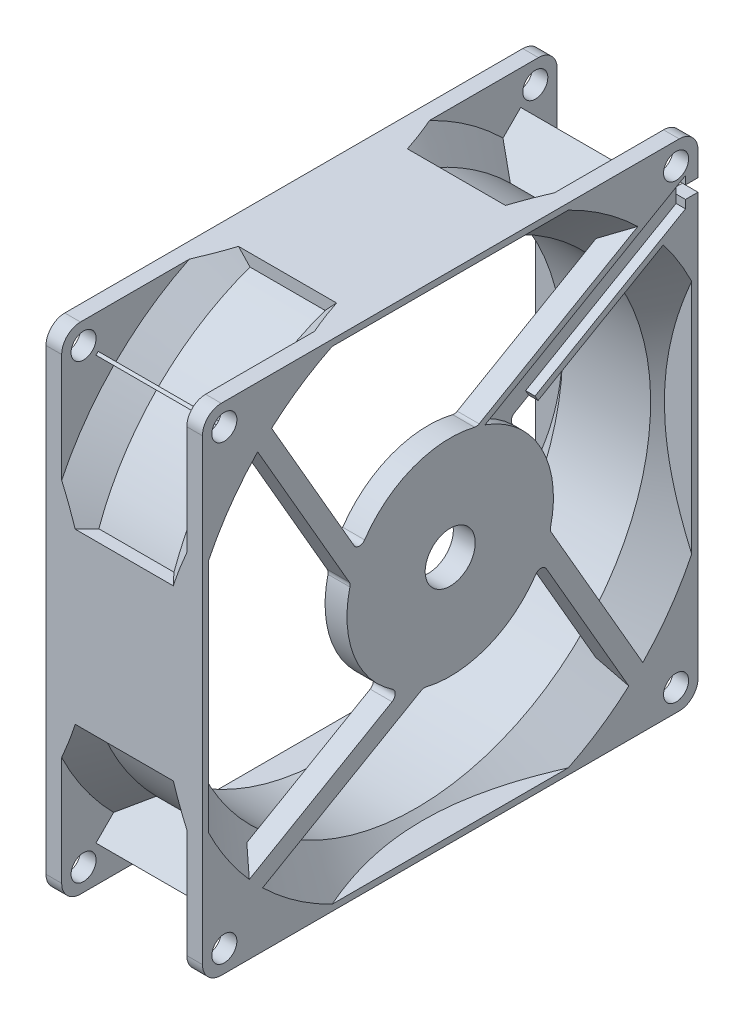
SolidWorks part; units mm, degrees
ref_plane "Front Plane" through (0, 0, 0) normal (0, 0, 1) x (1, 0, 0)
ref_plane "Top Plane" through (0, 0, 0) normal (0, 1, 0) x (1, 0, 0)
ref_plane "Right Plane" through (0, 0, 0) normal (1, 0, 0) x (0, 0, -1)
sketch "Sketch1" plane through (0, 0, 0) normal (0, 0, 1) x (1, 0, 0)
  line L0 (-10, 56) -> (-10, 44)
  line L1 (-10, 44) -> (-6, 40)
  line L2 (-6, 40) -> (6, 40)
  line L3 (6, 40) -> (10, 44)
  line L4 (10, 44) -> (10, 56)
  line L5 (-12.5, 56) -> (-12.5, 42.9645)
  line L6 (-12.5, 42.9645) -> (-7.0355, 37.5)
  line L7 (-7.0355, 37.5) -> (7.0355, 37.5)
  line L8 (7.0355, 37.5) -> (12.5, 42.9645)
  line L9 (12.5, 42.9645) -> (12.5, 56)
  line L10 (-12.5, 56) -> (-10, 56)
  line L11 (10, 56) -> (12.5, 56)
  line L12 (-12.5, 0) -> (13.9887, 0) construction
  point P8 (0, 40)
  dimension "D1" = 12
  dimension "D2" = 4
  dimension "D3" = 12
  dimension "D4" = 45
  dimension "D5" = 40
  dimension "D6" = 45
  dimension "D7" = 2.5
revolve "Revolve1" add sketch "Sketch1" angle 360 about L12
sketch "Sketch2" plane through (12.5, 0, 0) normal (1, 0, 0) x (0, 0, -1)
  line L1 (-39.598, 39.598) -> (39.598, 39.598)
  line L2 (-39.598, 39.598) -> (-39.598, -39.598)
  line L3 (-39.598, -39.598) -> (39.598, -39.598)
  line L4 (39.598, 39.598) -> (39.598, -39.598)
  line L5 (-39.598, 39.598) -> (39.598, -39.598) construction
  line L6 (-39.598, -39.598) -> (39.598, 39.598) construction
  circle A0 centre (0, 0) radius 56 construction
  point P0 (0, 0)
extrude "Cut-Extrude1" cut sketch "Sketch2" against normal through all flip side to cut
sketch "Sketch3" plane through (12.5, 0, 0) normal (1, 0, 0) x (0, 0, -1)
  line L0 (-16.6717, 39.598) -> (-39.598, 39.598) construction
  line L1 (-18.8717, 39.598) -> (18.8717, 39.598)
  line L2 (-18.8717, 39.598) -> (-18.8717, 38.598)
  line L3 (-18.8717, 38.598) -> (18.8717, 38.598)
  line L4 (18.8717, 39.598) -> (18.8717, 38.598)
  arc A0 (39.598, 16.6717) -> (16.6717, 39.598) centre (0, 0) ccw construction
  arc A2 (-16.6717, 39.598) -> (-39.598, 16.6717) centre (0, 0) ccw construction
  dimension "D1" = 1
extrude "Boss-Extrude1" add sketch "Sketch3" against normal up to body
pattern_circular "CirPattern1" count 4 over 360 about axis through (0, 0, 0) along (1, 0, 0) of "Boss-Extrude1"
mirror "Mirror1" about plane through (0, 0, 0) normal (1, 0, 0) of "CirPattern1", "Boss-Extrude1"
sketch "Sketch4" plane through (0, 0, 0) normal (1, 0, 0) x (0, 0, -1)
  line L0 (0, 0) -> (39.598, 39.598) construction
  line L1 (33.7643, 34.1179) -> (26.3391, 26.6927)
  line L2 (33.7643, 34.1179) -> (34.1179, 33.7643)
  line L3 (26.3391, 26.6927) -> (26.6927, 26.3391)
  line L4 (34.1179, 33.7643) -> (26.6927, 26.3391)
  circle A0 centre (0, 0) radius 37.5 construction
  point P4 (26.5159, 26.5159)
  point P14 (33.9411, 33.9411)
  dimension "D1" = 0.5
  dimension "D2" = 48
extrude "Boss-Extrude2" add sketch "Sketch4" along normal up to body and the other way up to body
pattern_circular "CirPattern2" count 4 over 360 about axis through (0, 0, 0) along (1, 0, 0) of "Boss-Extrude2"
sketch "Sketch5" plane through (12.5, 0, 0) normal (1, 0, 0) x (0, 0, -1)
  line L0 (-39.598, -39.598) -> (39.598, -39.598) construction
  line L1 (39.598, -39.598) -> (39.598, 39.598) construction
  circle A0 centre (36.098, -36.098) radius 2
  dimension "D1" = 4
  dimension "D2" = 3.5
  dimension "D3" = 3.5
extrude "Cut-Extrude2" cut sketch "Sketch5" against normal through all separate body
pattern_circular "CirPattern3" count 4 over 360 about axis through (0, 0, 0) along (1, 0, 0) of "Cut-Extrude2"
fillet "Fillet1" radius 3 8 edges at (-11.25, 39.598, -39.598) (11.25, 39.598, -39.598) (-11.25, -39.598, -39.598) (11.25, -39.598, -39.598) (-11.25, -39.598, 39.598) (11.25, -39.598, 39.598) (-11.25, 39.598, 39.598) (11.25, 39.598, 39.598)
sketch "Sketch6" plane through (12.5, 0, 0) normal (1, 0, 0) x (0, 0, -1)
  line L0 (0, 39.598) -> (0, -39.598) construction
  line L1 (36.598, 39.598) -> (-36.598, 39.598) construction
  line L2 (-36.598, -39.598) -> (36.598, -39.598) construction
  line L3 (-39.598, 0) -> (39.598, 0) construction
  line L4 (-39.598, 36.598) -> (-39.598, -36.598) construction
  line L5 (39.598, -36.598) -> (39.598, 36.598) construction
  line L6 (29.9765, 30.7791) -> (4.2705, 15.9378)
  line L7 (10.5865, 12.6561) -> (34.0496, 26.2025)
  line L8 (0, 0) -> (4.2705, 15.9378) construction
  line L9 (-14.5262, 7.8256) -> (-28.5466, 32.1097)
  line L10 (-30.7791, 29.9765) -> (-15.9378, 4.2705)
  line L11 (0, 0) -> (-15.9378, 4.2705) construction
  line L12 (29.9765, 30.7791) -> (4.2705, 15.9378) [skipped]
  line L13 (7.8256, 14.5262) -> (32.1097, 28.5466) [skipped]
  line L14 (30.7791, -29.9765) -> (15.9378, -4.2705)
  line L15 (14.5262, -7.8256) -> (28.5466, -32.1097)
  line L16 (-29.9765, -30.7791) -> (-4.2705, -15.9378)
  line L17 (-7.8256, -14.5262) -> (-32.1097, -28.5466)
  arc A0 (-15.9378, 4.2705) -> (-7.8256, -14.5262) centre (0, 0) ccw
  arc A1 (18.8717, -38.598) -> (38.598, -18.8717) centre (0, 0) ccw construction
  arc A2 (-38.598, -18.8717) -> (-18.8717, -38.598) centre (0, 0) ccw construction
  arc A3 (-18.8717, 38.598) -> (-38.598, 18.8717) centre (0, 0) ccw construction
  arc A4 (38.598, 18.8717) -> (18.8717, 38.598) centre (0, 0) ccw construction
  arc A5 (28.5466, -32.1097) -> (30.7791, -29.9765) centre (0, 0) ccw
  arc A6 (-32.1097, -28.5466) -> (-29.9765, -30.7791) centre (0, 0) ccw
  arc A7 (-28.5466, 32.1097) -> (-30.7791, 29.9765) centre (0, 0) ccw
  arc A8 (34.0496, 26.2025) -> (29.9765, 30.7791) centre (0, 0) ccw
  arc A9 (4.2705, 15.9378) -> (-14.5262, 7.8256) centre (0, 0) ccw
  arc A10 (15.9378, -4.2705) -> (10.5865, 12.6561) centre (0, 0) ccw
  arc A11 (-4.2705, -15.9378) -> (14.5262, -7.8256) centre (0, 0) ccw
  circle A12 centre (0, 0) radius 4
  point P50 (0, 0)
  dimension "D1" = 33
  dimension "D9" = 8
  dimension "D2" = 6
  dimension "D3" = 30
  dimension "D4" = 15
  dimension "D5" = 3
  dimension "D6" = 30
  dimension "D7" = 15
  dimension "D8" = 4
extrude "Boss-Extrude3" add sketch "Sketch6" against normal blind 3.5
sketch "Sketch7" plane through (12.5, 0, 0) normal (1, 0, 0) x (0, 0, -1)
  line L0 (5.568, 15.5322) -> (37.598, 34.0247)
  line L1 (37.598, 34.0247) -> (37.598, 32.7153)
  line L2 (37.598, 32.7153) -> (39.598, 32.7153)
  line L3 (39.598, -36.598) -> (39.598, 36.598) construction
  line L4 (39.598, 32.7153) -> (39.598, 30.7153)
  line L5 (39.598, 30.7153) -> (37.598, 30.7153)
  line L6 (37.598, 30.7153) -> (37.598, 29.4059)
  line L7 (37.598, 29.4059) -> (13.5506, 15.5221)
  line L8 (13.5506, 15.5221) -> (14.0506, 14.6561)
  line L10 (10.5865, 12.6561) -> (34.0496, 26.2025) construction
  line L11 (14.0506, 14.6561) -> (10.5865, 12.6561)
  line L12 (29.9765, 30.7791) -> (4.2705, 15.9378) construction
  arc A0 (5.568, 15.5322) -> (10.5865, 12.6561) centre (0, 0) cw
  dimension "D1" = 4
  dimension "D2" = 1
  dimension "D3" = 1
  dimension "D4" = 2
  dimension "D5" = 2
extrude "Cut-Extrude3" cut sketch "Sketch7" against normal blind 1.5
sketch "Sketch8" plane through (11, 0, 0) normal (1, 0, 0) x (0, 0, -1)
  line L1 (37.598, 32.7153) -> (39.598, 32.7153)
  line L2 (37.598, 32.7153) -> (37.598, 30.7153)
  line L3 (37.598, 30.7153) -> (39.598, 30.7153)
  line L4 (39.598, 32.7153) -> (39.598, 30.7153)
extrude "Cut-Extrude4" cut sketch "Sketch8" against normal up to next
fillet "Fillet2" radius 1 8 edges at (10.75, -7.8256, -14.5262) (10.75, -4.2705, -15.9378) (10, 12.6561, -10.5865) (10.75, 15.9378, -4.2705) (10.75, 7.8256, 14.5262) (10.75, 4.2705, 15.9378) (10.75, -14.5262, 7.8256) (10.75, -15.9378, 4.2705)
sketch "Sketch9" plane through (0, 0, -39.598) normal (0, 0, -1) x (-1, 0, 0)
  line L1 (-10, 13.5) -> (10, 13.5)
  line L2 (-10, 13.5) -> (-10, -13.5)
  line L3 (-10, -13.5) -> (10, -13.5)
  line L4 (10, 13.5) -> (10, -13.5)
  line L8 (-10, 19.1833) -> (-10, 30.9354) construction
  line L9 (10, 30.9354) -> (10, 19.1833) construction
  point P8 (10, 0)
  dimension "D1" = 27
extrude "Boss-Extrude4" add sketch "Sketch9" against normal up to body
pattern_circular "CirPattern4" count 4 over 360 about axis through (0, 0, 0) along (1, 0, 0) of "Boss-Extrude4"
